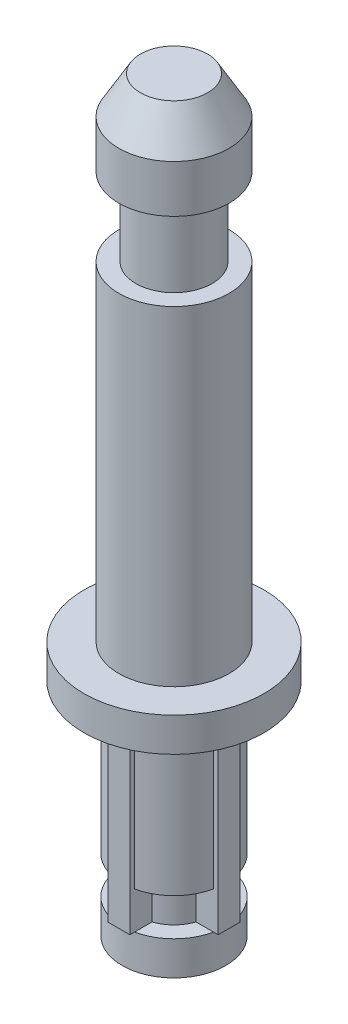
SolidWorks part; units mm, degrees
ref_plane "Front Plane" through (0, 0, 0) normal (0, 0, 1) x (1, 0, 0)
ref_plane "Top Plane" through (0, 0, 0) normal (0, 1, 0) x (1, 0, 0)
ref_plane "Right Plane" through (0, 0, 0) normal (1, 0, 0) x (0, 0, -1)
sketch "Эскиз1" plane through (0, 0, 0) normal (0, 1, 0) x (1, 0, 0)
  circle A0 centre (0, 0) radius 3.25
  dimension "D1" = 6.5
extrude "Бобышка-Вытянуть1" add sketch "Эскиз1" along normal blind 29
sketch "Эскиз2" plane through (0, 29, 0) normal (0, 1, 0) x (1, 0, 0)
  circle A0 centre (0, 0) radius 2.25
  dimension "D1" = 4.5
extrude "Вырез-Вытянуть1" cut sketch "Эскиз2" against normal blind 4.6 from offset 5 flip side to cut offset against normal yes
chamfer "Фаска1" distance 2.2 angle 30 1 edges at (0, 29, 3.25)
sketch "Эскиз3" plane through (0, 0, 0) normal (0, -1, 0) x (1, 0, 0)
  circle A0 centre (0, 0) radius 5.3
  dimension "D1" = 10.6
extrude "Бобышка-Вытянуть2" add sketch "Эскиз3" along normal blind 2
sketch "Эскиз4" plane through (0, -2, 0) normal (0, -1, 0) x (1, 0, 0)
  line L2 (-0.65, 3.25) -> (0.65, 3.25)
  line L3 (-0.65, 3.25) -> (-0.65, 2.9799)
  line L4 (-0.65, -3.25) -> (0.65, -3.25)
  line L5 (0.65, 3.25) -> (0.65, 2.9799)
  line L6 (-0.65, 3.25) -> (0.65, -3.25) construction
  line L7 (-0.65, -3.25) -> (0.65, 3.25) construction
  line L8 (-3.25, 0.65) -> (-2.9799, 0.65)
  line L9 (-3.25, 0.65) -> (-3.25, -0.65)
  line L10 (-3.25, -0.65) -> (-2.9799, -0.65)
  line L11 (3.25, 0.65) -> (3.25, -0.65)
  line L12 (-3.25, 0.65) -> (3.25, -0.65) construction
  line L13 (-3.25, -0.65) -> (3.25, 0.65) construction
  line L17 (2.9799, 0.65) -> (3.25, 0.65)
  line L18 (0.65, -2.9799) -> (0.65, -3.25)
  line L19 (-0.65, -2.9799) -> (-0.65, -3.25)
  line L20 (2.9799, -0.65) -> (3.25, -0.65)
  arc A0 (-2.9799, -0.65) -> (-0.65, -2.9799) centre (0, 0) ccw
  arc A1 (-0.65, 2.9799) -> (-2.9799, 0.65) centre (0, 0) ccw
  arc A2 (2.9799, 0.65) -> (0.65, 2.9799) centre (0, 0) ccw
  arc A3 (0.65, -2.9799) -> (2.9799, -0.65) centre (0, 0) ccw
  point P1 (0, 0)
  point P16 (0, 0)
  dimension "D1" = 6.1
  dimension "D2" = 1.3
extrude "Бобышка-Вытянуть3" add sketch "Эскиз4" along normal blind 13
sketch "Эскиз5" plane through (0, -15, 0) normal (0, -1, 0) x (1, 0, 0)
  line L0 (-2.9799, 0.65) -> (-1.9442, 0.65)
  line L1 (2.9799, 0.65) -> (1.9442, 0.65)
  line L2 (-0.65, 2.9799) -> (-0.65, 1.9442)
  line L3 (-0.65, -1.9442) -> (-0.65, -2.9799)
  line L4 (0.65, 2.9799) -> (0.65, 1.9442)
  line L5 (0.65, -2.9799) -> (0.65, -1.9442)
  line L7 (2.9799, -0.65) -> (1.9442, -0.65)
  line L8 (-2.9799, -0.65) -> (-1.9442, -0.65)
  arc A0 (0.65, -1.9442) -> (1.9442, -0.65) centre (0, 0) ccw
  arc A1 (-0.65, 2.9799) -> (-2.9799, 0.65) centre (0, 0) ccw construction
  arc A2 (0.65, -2.9799) -> (2.9799, -0.65) centre (0, 0) ccw construction
  arc A3 (0.65, -2.9799) -> (2.9799, -0.65) centre (0, 0) ccw
  arc A4 (2.9799, 0.65) -> (0.65, 2.9799) centre (0, 0) ccw construction
  arc A5 (2.9799, 0.65) -> (0.65, 2.9799) centre (0, 0) ccw
  arc A6 (-0.65, 2.9799) -> (-2.9799, 0.65) centre (0, 0) ccw construction
  arc A7 (-0.65, 2.9799) -> (-2.9799, 0.65) centre (0, 0) ccw
  arc A8 (-2.9799, -0.65) -> (-0.65, -2.9799) centre (0, 0) ccw construction
  arc A9 (-2.9799, -0.65) -> (-0.65, -2.9799) centre (0, 0) ccw
  arc A10 (1.9442, 0.65) -> (0.65, 1.9442) centre (0, 0) ccw
  arc A11 (-0.65, 1.9442) -> (-1.9442, 0.65) centre (0, 0) ccw
  arc A12 (-1.9442, -0.65) -> (-0.65, -1.9442) centre (0, 0) ccw
  dimension "D1" = 1
extrude "Вырез-Вытянуть2" cut sketch "Эскиз5" against normal blind 2.2 from offset 2 offset against normal yes
sketch "Эскиз6" plane through (0, -15, 0) normal (0, -1, 0) x (1, 0, 0)
  circle A0 centre (0, 0) radius 3.05
extrude "Вырез-Вытянуть3" cut sketch "Эскиз6" against normal up to surface (2 mm away) flip side to cut up to face at (-1.6796, -13, 1.6796)
